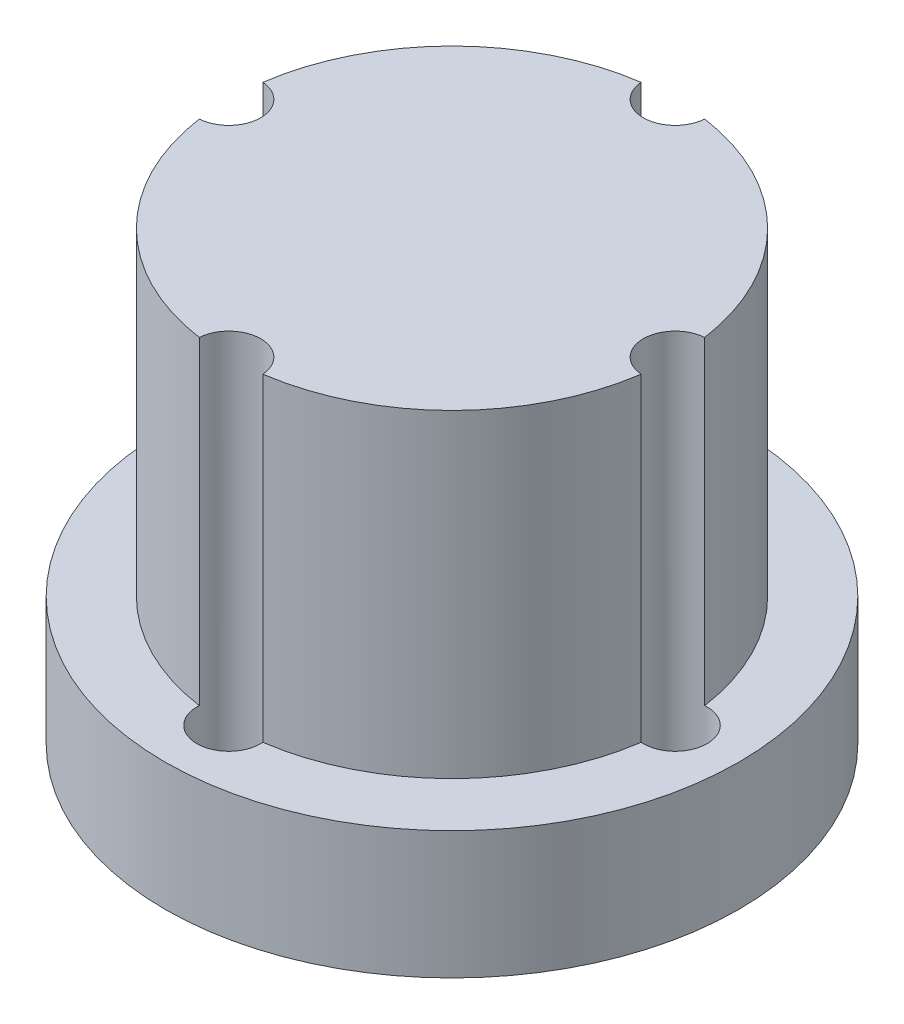
SolidWorks part; units mm, degrees
ref_plane "Спереди" through (0, 0, 0) normal (0, 0, 1) x (1, 0, 0)
ref_plane "Сверху" through (0, 0, 0) normal (0, 1, 0) x (1, 0, 0)
ref_plane "Справа" through (0, 0, 0) normal (1, 0, 0) x (0, 0, -1)
sketch "Эскиз1" plane through (0, 0, 0) normal (0, 1, 0) x (1, 0, 0)
  circle A0 centre (0, 0) radius 9
extrude "Бобышка-Вытянуть1" add sketch "Эскиз1" along normal blind 14
sketch "Эскиз2" plane through (0, 14, 0) normal (0, 1, 0) x (1, 0, 0)
  circle A0 centre (0, 0) radius 7 construction
  circle A1 centre (0, 7) radius 1
  circle A2 centre (7, 0) radius 1
  circle A3 centre (-7, 0) radius 1
  circle A4 centre (0, -7) radius 1
extrude "Вырез-Вытянуть1" cut sketch "Эскиз2" against normal blind 20
sketch "Эскиз3" plane through (0, 14, 0) normal (0, 1, 0) x (1, 0, 0)
  circle A0 centre (0, 0) radius 9
  circle A1 centre (0, 0) radius 7
extrude "Вырез-Вытянуть2" cut sketch "Эскиз3" against normal blind 10
